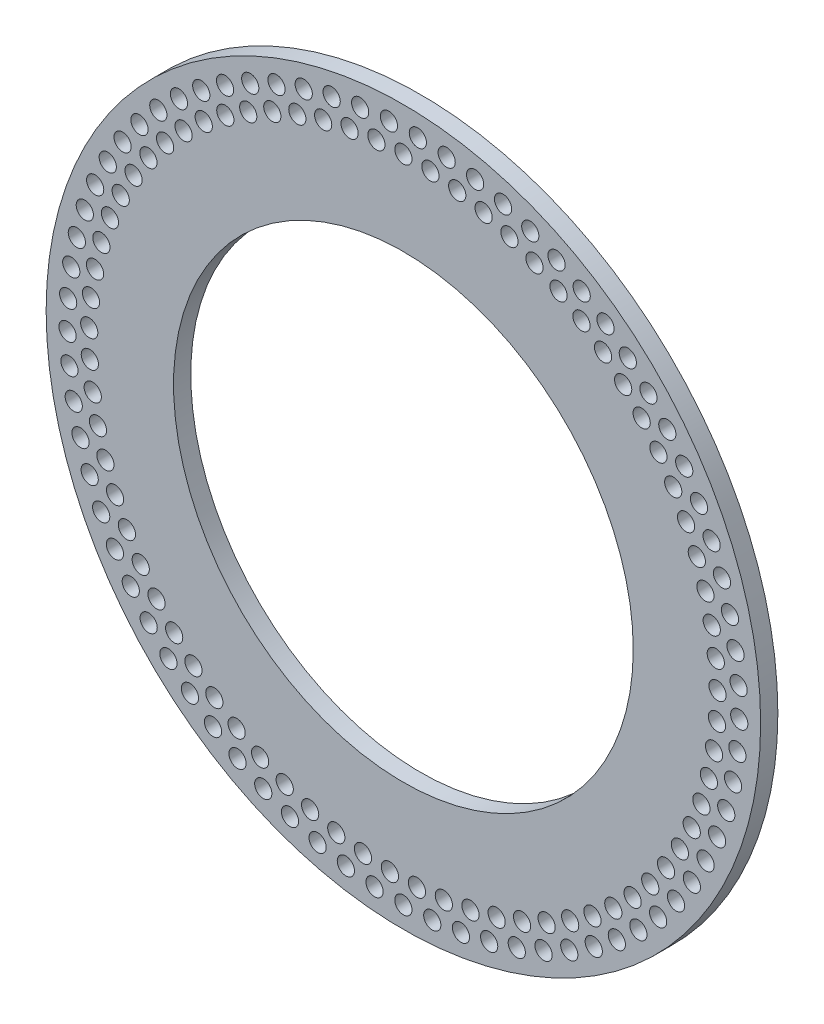
SolidWorks part; units mm, degrees
ref_plane "Ön Düzlem" through (0, 0, 0) normal (0, 0, 1) x (1, 0, 0)
ref_plane "Üst Düzlem" through (0, 0, 0) normal (0, 1, 0) x (1, 0, 0)
ref_plane "Sağ Düzlem" through (0, 0, 0) normal (1, 0, 0) x (0, 0, -1)
sketch "Çizim1" plane through (0, 0, 0) normal (0, 0, 1) x (1, 0, 0)
  circle A0 centre (0, 0) radius 41.5
  dimension "D1" = 83
extrude "Yükseklik-Ekstrüzyon1" add sketch "Çizim1" along normal blind 2
sketch "Çizim2" plane through (0, 0, 2) normal (0, 0, 1) x (1, 0, 0)
  circle A0 centre (0, 0) radius 26.7
  dimension "D1" = 53.4
extrude "Kes-Ekstrüzyon1" cut sketch "Çizim2" against normal blind 3
sketch "Çizim3" plane through (0, 0, 0) normal (0, 0, -1) x (-1, 0, 0)
  circle A0 centre (0, 36.5) radius 1
  circle A1 centre (3.1377, 36.3649) radius 1
  circle A2 centre (6.2522, 35.9605) radius 1
  circle A3 centre (9.3204, 35.2899) radius 1
  circle A4 centre (12.3196, 34.3581) radius 1
  circle A5 centre (15.2276, 33.1718) radius 1
  circle A6 centre (18.0228, 31.74) radius 1
  circle A7 centre (20.6846, 30.0732) radius 1
  circle A8 centre (23.1933, 28.1837) radius 1
  circle A9 centre (25.5302, 26.0856) radius 1
  circle A10 centre (27.6782, 23.7943) radius 1
  circle A11 centre (29.6212, 21.3269) radius 1
  circle A12 centre (31.3449, 18.7016) radius 1
  circle A13 centre (32.8365, 15.9378) radius 1
  circle A14 centre (34.0851, 13.056) radius 1
  circle A15 centre (35.0812, 10.0775) radius 1
  circle A16 centre (35.8177, 7.0245) radius 1
  circle A17 centre (36.289, 3.9194) radius 1
  circle A18 centre (36.4916, 0.7853) radius 1
  circle A19 centre (36.424, -2.3546) radius 1
  circle A20 centre (36.0867, -5.477) radius 1
  circle A21 centre (35.4823, -8.5589) radius 1
  circle A22 centre (34.6152, -11.5775) radius 1
  circle A23 centre (33.4918, -14.5103) radius 1
  circle A24 centre (32.1204, -17.3357) radius 1
  circle A25 centre (30.5113, -20.0328) radius 1
  circle A26 centre (28.6762, -22.5815) radius 1
  circle A27 centre (26.6289, -24.9631) radius 1
  circle A28 centre (24.3843, -27.1598) radius 1
  circle A29 centre (21.9593, -29.1554) radius 1
  circle A30 centre (19.3716, -30.9352) radius 1
  circle A31 centre (16.6406, -32.486) radius 1
  circle A32 centre (13.7863, -33.7963) radius 1
  circle A33 centre (10.83, -34.8563) radius 1
  circle A34 centre (7.7935, -35.6583) radius 1
  circle A35 centre (4.6993, -36.1962) radius 1
  circle A36 centre (1.5703, -36.4662) radius 1
  circle A37 centre (-1.5703, -36.4662) radius 1
  circle A38 centre (-4.6993, -36.1962) radius 1
  circle A39 centre (-7.7935, -35.6583) radius 1
  circle A40 centre (-10.83, -34.8563) radius 1
  circle A41 centre (-13.7863, -33.7963) radius 1
  circle A42 centre (-16.6406, -32.486) radius 1
  circle A43 centre (-19.3716, -30.9352) radius 1
  circle A44 centre (-21.9593, -29.1554) radius 1
  circle A45 centre (-24.3843, -27.1598) radius 1
  circle A46 centre (-26.6289, -24.9631) radius 1
  circle A47 centre (-28.6762, -22.5815) radius 1
  circle A48 centre (-30.5113, -20.0328) radius 1
  circle A49 centre (-32.1204, -17.3357) radius 1
  circle A50 centre (-33.4918, -14.5103) radius 1
  circle A51 centre (-34.6152, -11.5775) radius 1
  circle A52 centre (-35.4823, -8.5589) radius 1
  circle A53 centre (-36.0867, -5.477) radius 1
  circle A54 centre (-36.424, -2.3546) radius 1
  circle A55 centre (-36.4916, 0.7853) radius 1
  circle A56 centre (-36.289, 3.9194) radius 1
  circle A57 centre (-35.8177, 7.0245) radius 1
  circle A58 centre (-35.0812, 10.0775) radius 1
  circle A59 centre (-34.0851, 13.056) radius 1
  circle A60 centre (-32.8365, 15.9378) radius 1
  circle A61 centre (-31.3449, 18.7016) radius 1
  circle A62 centre (-29.6212, 21.3269) radius 1
  circle A63 centre (-27.6782, 23.7943) radius 1
  circle A64 centre (-25.5302, 26.0856) radius 1
  circle A65 centre (-23.1933, 28.1837) radius 1
  circle A66 centre (-20.6846, 30.0732) radius 1
  circle A67 centre (-18.0228, 31.74) radius 1
  circle A68 centre (-15.2276, 33.1718) radius 1
  circle A69 centre (-12.3196, 34.3581) radius 1
  circle A70 centre (-9.3204, 35.2899) radius 1
  circle A71 centre (-6.2522, 35.9605) radius 1
  circle A72 centre (-3.1377, 36.3649) radius 1
  circle A74 centre (-1.6788, 38.9863) radius 1
  circle A75 centre (1.6788, 38.9863) radius 1
  circle A76 centre (5.0241, 38.6976) radius 1
  circle A77 centre (8.3321, 38.1225) radius 1
  circle A78 centre (11.5784, 37.2651) radius 1
  circle A79 centre (14.7391, 36.1318) radius 1
  circle A80 centre (17.7906, 34.731) radius 1
  circle A81 centre (20.7104, 33.0731) radius 1
  circle A82 centre (23.4768, 31.1703) radius 1
  circle A83 centre (26.0695, 29.0367) radius 1
  circle A84 centre (28.4691, 26.6882) radius 1
  circle A85 centre (30.6579, 24.142) radius 1
  circle A86 centre (32.6198, 21.4172) radius 1
  circle A87 centre (34.3402, 18.5337) radius 1
  circle A88 centre (35.8063, 15.5131) radius 1
  circle A89 centre (37.0073, 12.3776) radius 1
  circle A90 centre (37.9344, 9.1504) radius 1
  circle A91 centre (38.5806, 5.8555) radius 1
  circle A92 centre (38.9411, 2.5173) radius 1
  circle A93 centre (39.0134, -0.8396) radius 1
  circle A94 centre (38.7968, -4.1903) radius 1
  circle A95 centre (38.2929, -7.5099) radius 1
  circle A96 centre (37.5056, -10.774) radius 1
  circle A97 centre (36.4406, -13.9582) radius 1
  circle A98 centre (35.1058, -17.0392) radius 1
  circle A99 centre (33.511, -19.994) radius 1
  circle A100 centre (31.6682, -22.8007) radius 1
  circle A101 centre (29.5909, -25.4387) radius 1
  circle A102 centre (27.2945, -27.8883) radius 1
  circle A103 centre (24.7961, -30.1314) radius 1
  circle A104 centre (22.1141, -32.1515) radius 1
  circle A105 centre (19.2683, -33.9335) radius 1
  circle A106 centre (16.2799, -35.4642) radius 1
  circle A107 centre (13.171, -36.7325) radius 1
  circle A108 centre (9.9645, -37.7287) radius 1
  circle A109 centre (6.6843, -38.4457) radius 1
  circle A110 centre (3.3546, -38.8779) radius 1
  circle A111 centre (0, -39.0224) radius 1
  circle A112 centre (-3.3546, -38.8779) radius 1
  circle A113 centre (-6.6843, -38.4457) radius 1
  circle A114 centre (-9.9645, -37.7287) radius 1
  circle A115 centre (-13.171, -36.7325) radius 1
  circle A116 centre (-16.2799, -35.4642) radius 1
  circle A117 centre (-19.2683, -33.9335) radius 1
  circle A118 centre (-22.1141, -32.1515) radius 1
  circle A119 centre (-24.7961, -30.1314) radius 1
  circle A120 centre (-27.2945, -27.8883) radius 1
  circle A121 centre (-29.5909, -25.4387) radius 1
  circle A122 centre (-31.6682, -22.8007) radius 1
  circle A123 centre (-33.511, -19.994) radius 1
  circle A124 centre (-35.1058, -17.0392) radius 1
  circle A125 centre (-36.4406, -13.9582) radius 1
  circle A126 centre (-37.5056, -10.774) radius 1
  circle A127 centre (-38.2929, -7.5099) radius 1
  circle A128 centre (-38.7968, -4.1903) radius 1
  circle A129 centre (-39.0134, -0.8396) radius 1
  circle A130 centre (-38.9411, 2.5173) radius 1
  circle A131 centre (-38.5806, 5.8555) radius 1
  circle A132 centre (-37.9344, 9.1504) radius 1
  circle A133 centre (-37.0073, 12.3776) radius 1
  circle A134 centre (-35.8063, 15.5131) radius 1
  circle A135 centre (-34.3402, 18.5337) radius 1
  circle A136 centre (-32.6198, 21.4172) radius 1
  circle A137 centre (-30.6579, 24.142) radius 1
  circle A138 centre (-28.4691, 26.6882) radius 1
  circle A139 centre (-26.0695, 29.0367) radius 1
  circle A140 centre (-23.4768, 31.1703) radius 1
  circle A141 centre (-20.7104, 33.0731) radius 1
  circle A142 centre (-17.7906, 34.731) radius 1
  circle A143 centre (-14.7391, 36.1318) radius 1
  circle A144 centre (-11.5784, 37.2651) radius 1
  circle A145 centre (-8.3321, 38.1225) radius 1
  circle A146 centre (-5.0241, 38.6976) radius 1
  point P150 (0, 0)
  point P297 (0, 0)
  dimension "D1" = 2
  dimension "D5" = 2
  dimension "D2" = 36.5
  dimension "D4" = 36.5
  dimension "D6" = 3
  dimension "D7" = 3
  dimension "D3" = 73
  dimension "D8" = 73
extrude "Kes-Ekstrüzyon2" cut sketch "Çizim3" against normal blind 3
